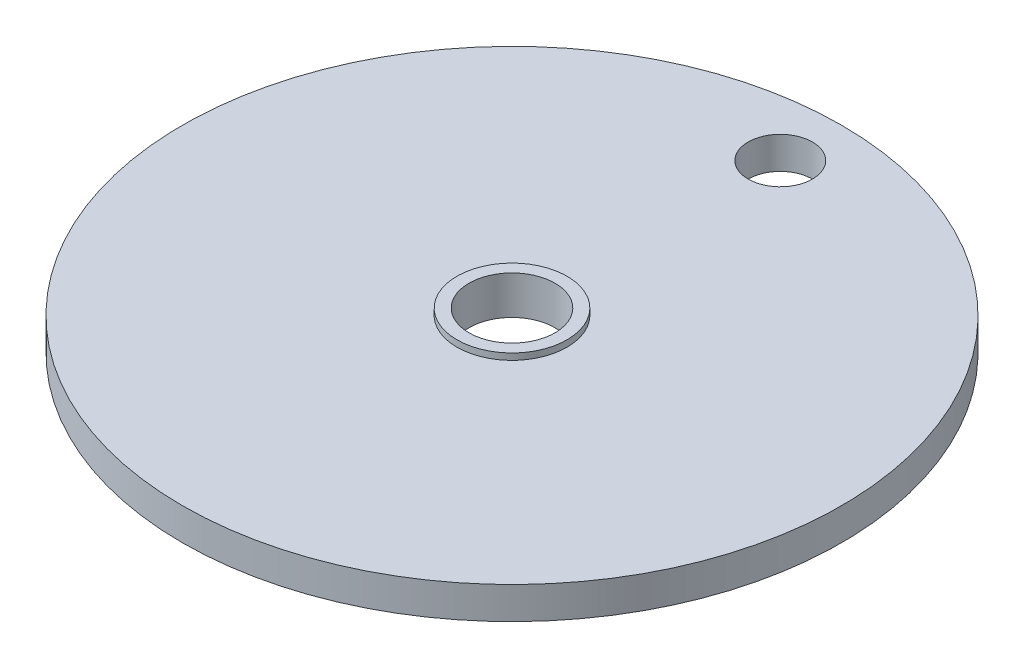
SolidWorks part; units mm, degrees
ref_plane "Front Plane" through (0, 0, 0) normal (0, 0, 1) x (1, 0, 0)
ref_plane "Top Plane" through (0, 0, 0) normal (0, 1, 0) x (1, 0, 0)
ref_plane "Right Plane" through (0, 0, 0) normal (1, 0, 0) x (0, 0, -1)
sketch "Sketch1" plane through (0, 0, 0) normal (0, 1, 0) x (1, 0, 0)
  circle A0 centre (0, 0) radius 20.5
  dimension "D1" = 41
extrude "Boss-Extrude1" add sketch "Sketch1" along normal blind 2
sketch "Sketch2" plane through (0, 2, 0) normal (0, 1, 0) x (1, 0, 0)
  circle A0 centre (0, 0) radius 2.675
  dimension "D1" = 5.35
extrude "Cut-Extrude1" cut sketch "Sketch2" against normal blind 2
sketch "Sketch3" plane through (0, 2, 0) normal (0, 1, 0) x (1, 0, 0)
  circle A0 centre (0, 0) radius 3.425
  circle A1 centre (0, 0) radius 2.675
  dimension "D1" = 5.35
  dimension "D2" = 6.85
extrude "Boss-Extrude2" add sketch "Sketch3" along normal blind 0.4
sketch "Sketch4" plane through (0, 2, 0) normal (0, 1, 0) x (1, 0, 0)
  circle A0 centre (0, 16.6886) radius 2
  dimension "D1" = 4
extrude "Cut-Extrude2" cut sketch "Sketch4" against normal blind 2
